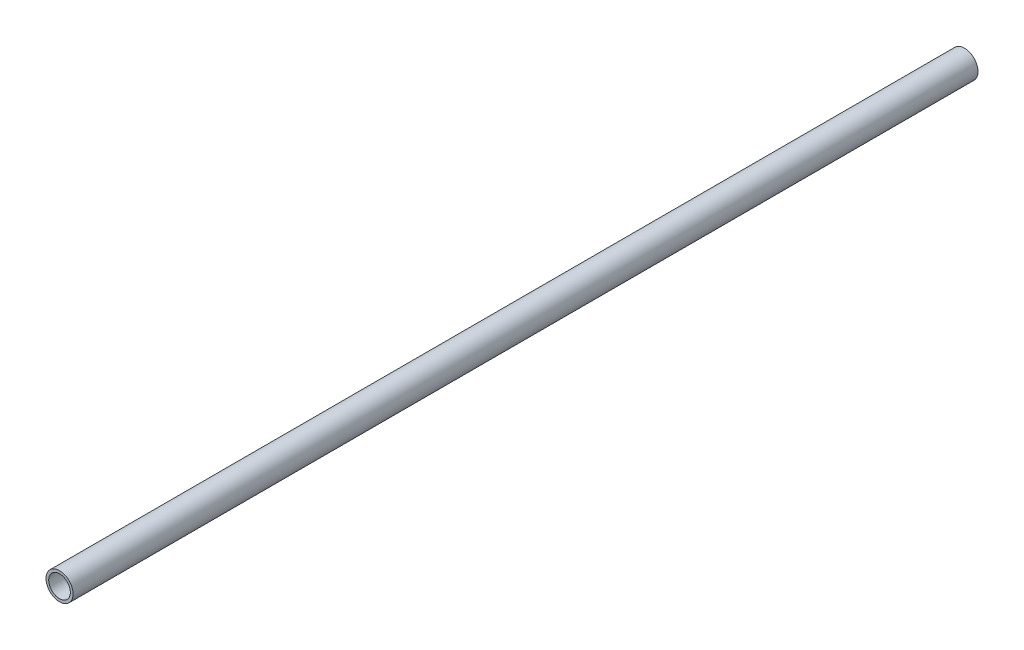
SolidWorks part; units mm, degrees
material "СТ3КП"
ref_plane "Спереди" through (0, 0, 0) normal (0, 0, 1) x (1, 0, 0)
ref_plane "Сверху" through (0, 0, 0) normal (0, 1, 0) x (1, 0, 0)
ref_plane "Справа" through (0, 0, 0) normal (1, 0, 0) x (0, 0, -1)
sketch "Эскиз1" plane through (0, 0, 0) normal (0, 0, 1) x (1, 0, 0)
  line L2 (1585.4946, 0) -> (-462.1132, 0) construction
  line L3 (0, 20) -> (0, 27) construction
  circle A0 centre (16, 16) radius 12.8
  circle A1 centre (16, 16) radius 16
  point P2 (17.0132, 16)
  dimension "D2" = 32
  dimension "D1" = 3.2
extrude "Бобышка-Вытянуть1" add sketch "Эскиз1" along normal offset from surface 30 and the other way offset from surface (1040 mm away) 30
